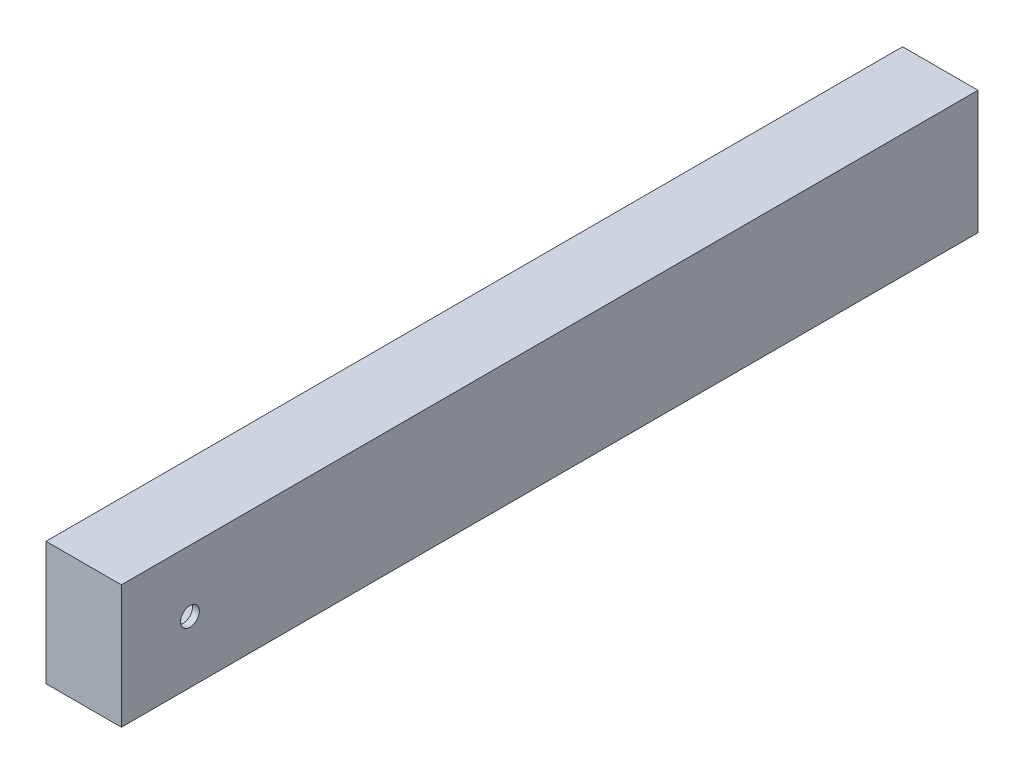
SolidWorks part; units mm, degrees
ref_plane "Plano frontal" through (0, 0, 0) normal (0, 0, 1) x (1, 0, 0)
ref_plane "Plano superior" through (0, 0, 0) normal (0, 1, 0) x (1, 0, 0)
ref_plane "Plano direito" through (0, 0, 0) normal (1, 0, 0) x (0, 0, -1)
sketch "Esboço1" plane through (0, 0, 0) normal (0, 0, 1) x (1, 0, 0)
  line L0 (0, 0) -> (11, 0)
  line L1 (11, 0) -> (11, 36)
  line L2 (11, 36) -> (-11, 36)
  line L3 (-11, 36) -> (-11, 0)
  line L4 (-11, 0) -> (0, 0)
  line L5 (0, 36) -> (0, 0)
  line L7 (-9, 2) -> (9, 2)
  line L8 (-9, 2) -> (-9, 34)
  line L9 (-9, 34) -> (9, 34)
  line L10 (9, 2) -> (9, 34)
  line L11 (-9, 2) -> (9, 34) construction
  line L12 (-9, 34) -> (9, 2) construction
  point P7 (0, 18)
  dimension "D1" = 11
  dimension "D2" = 36
  dimension "D3" = 22
  dimension "D4" = 32
  dimension "D5" = 18
extrude "Ressalto-extrusão1" add sketch "Esboço1" along normal blind 250 contours L10 L7 L5 L0 L1 L2 L9 | L8 L9 L5 L2 L3 L4 L7
shell "Casca1" thickness 2
sketch "Esboço2" plane through (0, 0, 0) normal (0, -1, 0) x (-1, 0, 0)
  line L0 (0, 0) -> (0, -20)
  circle A0 centre (0, -20) radius 5
  circle A1 centre (0, -40) radius 5
  circle A2 centre (0, -60) radius 5
  circle A3 centre (0, -80) radius 5
  circle A4 centre (0, -100) radius 5
  dimension "D2" = 10
  dimension "D1" = 20
  dimension "D3" = 5
extrude "Corte-extrusão1" cut sketch "Esboço2" against normal blind 10
sketch "Esboço3" plane through (11, 0, 0) normal (1, 0, 0) x (0, 0, -1)
  line L0 (-250, 18) -> (-230, 18)
  line L1 (-250, 0) -> (-250, 36) construction
  circle A0 centre (-230, 18) radius 2.75
  dimension "D2" = 5.5
  dimension "D1" = 20
extrude "Corte-extrusão2" cut sketch "Esboço3" against normal blind 29 contours A0
